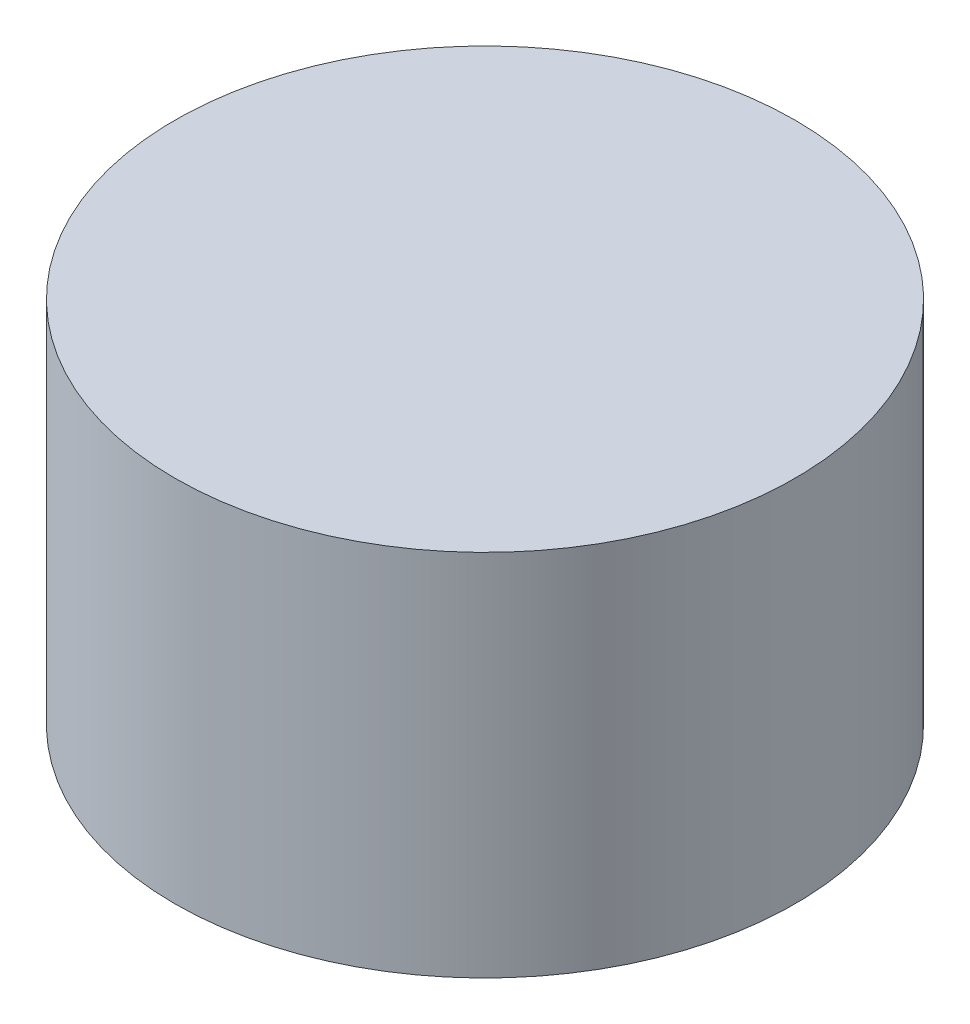
SolidWorks part; units mm, degrees
ref_plane "Front Plane" through (0, 0, 0) normal (0, 0, 1) x (1, 0, 0)
ref_plane "Top Plane" through (0, 0, 0) normal (0, 1, 0) x (1, 0, 0)
ref_plane "Right Plane" through (0, 0, 0) normal (1, 0, 0) x (0, 0, -1)
sketch "Sketch1" plane through (0, 0, 0) normal (0, 1, 0) x (1, 0, 0)
  circle A0 centre (0, 0) radius 11.1125
  dimension "D1" = 22.225
extrude "Boss-Extrude1" add sketch "Sketch1" along normal mid plane 13.208
sketch "Sketch2" plane through (0, 0, 0) normal (0, 1, 0) x (1, 0, 0)
  circle A0 centre (0, 0) radius 9.906
  dimension "D1" = 19.812
extrude "Boss-Extrude2" add sketch "Sketch2" along normal mid plane 12.7 separate body
sketch "Sketch3" plane through (0, 6.35, 0) normal (0, 1, 0) x (1, 0, 0)
  circle A0 centre (0, 0) radius 9.525
  circle A1 centre (0, 0) radius 9.906 construction
  circle A2 centre (0, 0) radius 9.906
  dimension "D1" = 19.05
extrude "Cut-Extrude1" cut sketch "Sketch3" against normal up to surface (6.096 mm away)
sketch "Sketch5" plane through (0, 0, 0) normal (0, 0, 1) x (1, 0, 0)
  line L0 (9.906, 0.254) -> (-9.906, 0.254) construction
  line L1 (-9.906, -6.35) -> (9.906, -6.35) construction
  line L2 (9.906, 0.254) -> (-9.906, 0.254) construction
  line L3 (-9.906, -6.35) -> (9.906, -6.35) construction
  line L4 (0, 0.254) -> (0, -6.35) construction
  line L5 (-9.906, 0.254) -> (-9.906, -1.016) construction
  line L6 (-9.906, 0.254) -> (-9.906, -6.35) construction
  line L7 (-9.906, -6.35) -> (-9.906, -5.08) construction
  circle A0 centre (-12.3456, -3.048) radius 3.175
  dimension "D1" = 6.35
  dimension "D2" = 1.27
revolve "Cut-Revolve1" cut sketch "Sketch5" angle 360 about L4
sketch "Sketch6" plane through (0, -6.35, 0) normal (0, -1, 0) x (1, 0, 0)
  circle A0 centre (0, 0) radius 6.35 construction
  circle A1 centre (0, 0) radius 6.35 construction
  circle A2 centre (0, 0) radius 6.604
extrude "Cut-Extrude3" cut sketch "Sketch6" against normal through all
equation "\"length\"= .5"
equation "\"cleanup\"= 0.01"
equation "\"precutLength\"= ( \"cleanup\" * 2 ) + \"length\""
equation "\"D1@Boss-Extrude1\"= \"precutLength\""
equation "\"diameter\"= 0.78"
equation "\"D1@Sketch2\"=\"diameter\""
equation "\"D1@Boss-Extrude2\"= \"length\""
equation "\"shoulder\"= 0.05"
equation "\"D2@Sketch5\"=\"shoulder\""
equation "\"cutRadius\"=0.25"
equation "\"handleOffset\"= 0.01"
equation "\"D1@Sketch6\"=\"handleOffset\""
